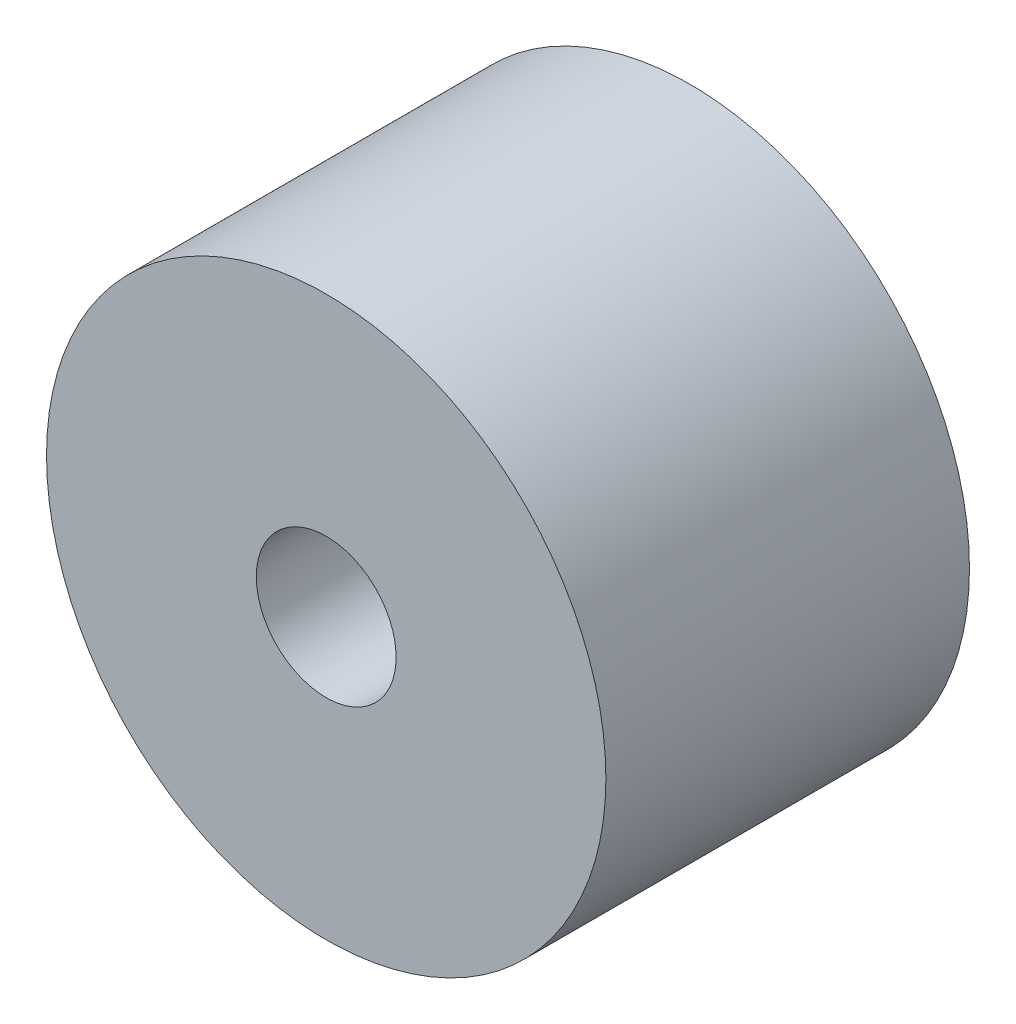
SolidWorks part; units mm, degrees
ref_plane "Front Plane" through (0, 0, 0) normal (0, 0, 1) x (1, 0, 0)
ref_plane "Top Plane" through (0, 0, 0) normal (0, 1, 0) x (1, 0, 0)
ref_plane "Right Plane" through (0, 0, 0) normal (1, 0, 0) x (0, 0, -1)
sketch "Sketch1" plane through (0, 0, 0) normal (0, 0, 1) x (1, 0, 0)
  circle A0 centre (0, 0) radius 10
  circle A1 centre (0, 0) radius 2.5
  circle A2 centre (0, 0) radius 8.0609
  dimension "D1" = 20
  dimension "D2" = 5
extrude "Boss-Extrude1" add sketch "Sketch1" along normal blind 13 contours A0 A2 | A2 A1
